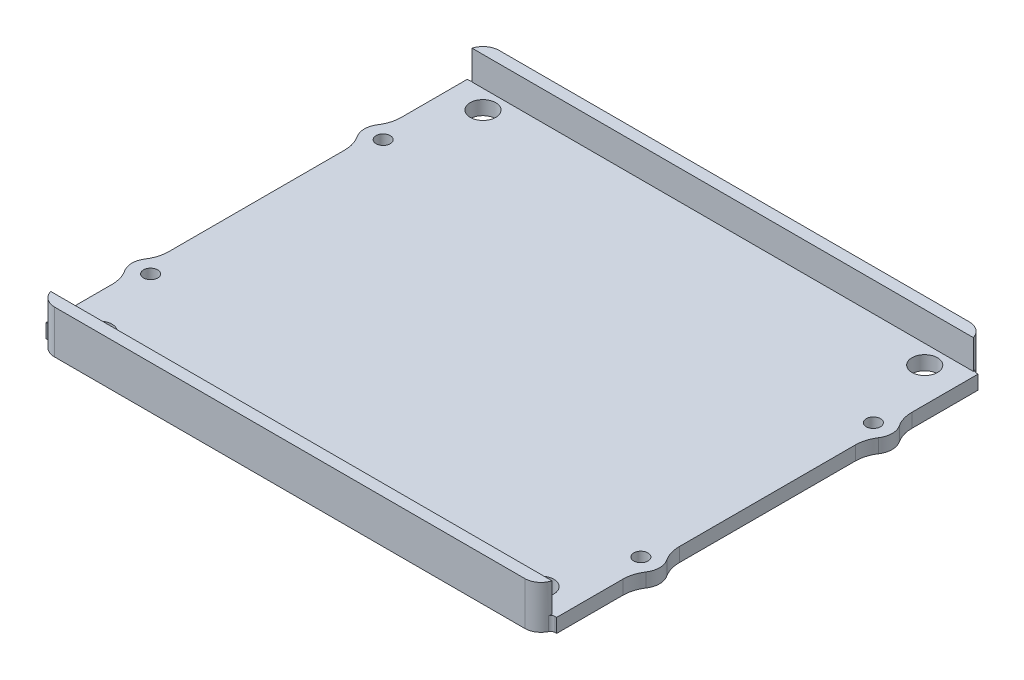
SolidWorks part; units mm, degrees
material "Hexcel AS4C (3000 Filaments)"
ref_plane "Front Plane" through (0, 0, 0) normal (0, 0, 1) x (1, 0, 0)
ref_plane "Top Plane" through (0, 0, 0) normal (0, 1, 0) x (1, 0, 0)
ref_plane "Right Plane" through (0, 0, 0) normal (1, 0, 0) x (0, 0, -1)
sketch "Sketch1" plane through (0, 0, 0) normal (0, 1, 0) x (1, 0, 0)
  line L1 (-50.55, -45.3) -> (50.55, -45.3)
  line L3 (-50.55, 45.3) -> (50.55, 45.3)
  line L7 (-50.55, 47.8) -> (50.55, 47.8)
  line L9 (-50.55, -47.8) -> (50.55, -47.8)
  line L10 (-50.55, 45.3) -> (-53.9041, 45.3)
  line L11 (-54.05, -44.3) -> (-54.05, 44.3) construction
  line L12 (-51.55, -44.3) -> (-51.55, 44.3) construction
  line L14 (-50.55, -45.3) -> (-53.9041, -45.3)
  line L16 (50.55, 45.3) -> (53.9041, 45.3)
  line L17 (50.55, -45.3) -> (53.9041, -45.3)
  line L18 (54.05, -44.3) -> (54.05, 44.3) construction
  line L19 (51.55, -44.3) -> (51.55, 44.3) construction
  arc A4 (-53.9041, 45.3) -> (-50.55, 47.8) centre (-50.55, 44.3) cw
  arc A5 (50.55, 47.8) -> (53.9041, 45.3) centre (50.55, 44.3) cw
  arc A6 (50.55, -47.8) -> (53.9041, -45.3) centre (50.55, -44.3) ccw
  arc A7 (-50.55, -47.8) -> (-53.9041, -45.3) centre (-50.55, -44.3) cw
  arc A8 (-51.55, 44.3) -> (-50.55, 45.3) centre (-50.55, 44.3) cw construction
  arc A9 (-54.05, 44.3) -> (-50.55, 47.8) centre (-50.55, 44.3) cw construction
  arc A10 (-50.55, -47.8) -> (-54.05, -44.3) centre (-50.55, -44.3) cw construction
  arc A11 (-50.55, -45.3) -> (-51.55, -44.3) centre (-50.55, -44.3) cw construction
  arc A12 (50.55, 47.8) -> (54.05, 44.3) centre (50.55, 44.3) cw construction
  arc A13 (50.55, 45.3) -> (51.55, 44.3) centre (50.55, 44.3) cw construction
  arc A14 (50.55, -47.8) -> (54.05, -44.3) centre (50.55, -44.3) ccw construction
  arc A15 (50.55, -45.3) -> (51.55, -44.3) centre (50.55, -44.3) ccw construction
  point P0 (0, 0)
  dimension "D4" = 2.5
extrude "Boss-Extrude1" add sketch "Sketch1" along normal blind 7.8 contours L16 A5 L7 A4 L10 L3 | L1 L17 A6 L9 A7 L14
sketch "Sketch3" plane through (0, 0, 0) normal (0, 1, 0) x (1, 0, 0)
  line L1 (-50.55, 47.8) -> (50.55, 47.8)
  line L3 (-50.55, -47.8) -> (50.55, -47.8)
  line L6 (-54.5811, 45.3) -> (-54.9091, 45.3)
  line L7 (-54.9091, 45.3) -> (-54.9091, -45.3)
  line L8 (-54.9091, -45.3) -> (-54.5811, -45.3)
  line L10 (54.9091, -45.3) -> (54.5811, -45.3)
  line L11 (54.9091, 45.3) -> (54.9091, -45.3)
  line L12 (54.5811, 45.3) -> (54.9091, 45.3)
  arc A14 (-53.6853, -45.8556) -> (-50.55, -47.8) centre (-50.55, -44.3) ccw
  arc A15 (-53.6853, 45.8556) -> (-50.55, 47.8) centre (-50.55, 44.3) cw
  arc A16 (50.55, 47.8) -> (53.6853, 45.8556) centre (50.55, 44.3) cw
  arc A17 (50.55, -47.8) -> (53.6853, -45.8556) centre (50.55, -44.3) ccw
  arc A18 (-53.6853, 45.8556) -> (-54.5811, 45.3) centre (-54.5811, 46.3) cw
  arc A19 (-53.6853, -45.8556) -> (-54.5811, -45.3) centre (-54.5811, -46.3) ccw
  arc A20 (53.6853, -45.8556) -> (54.5811, -45.3) centre (54.5811, -46.3) cw
  arc A21 (53.6853, 45.8556) -> (54.5811, 45.3) centre (54.5811, 46.3) ccw
  point P22 (-53.9041, 45.3)
  point P25 (-53.9041, -45.3)
  dimension "D2" = 1
  dimension "D1" = 1.005
extrude "Boss-Extrude2" add sketch "Sketch3" along normal mid plane 3
sketch "Sketch5" plane through (0, 1.5, 0) normal (0, 1, 0) x (1, 0, 0)
  circle A0 centre (-47.5, 41.25) radius 1.6
  circle A1 centre (47.5, 41.25) radius 1.6
  circle A2 centre (47.5, -41.25) radius 1.6
  circle A3 centre (-47.5, -41.25) radius 1.6
  dimension "D1" = 3.2
extrude "Cut-Extrude1" cut sketch "Sketch5" against normal through all
sketch "Sketch6" plane through (0, 1.5, 0) normal (0, 1, 0) x (1, 0, 0)
  line L0 (-54.9091, 45.3) -> (-54.9091, -45.3) construction
  circle A0 centre (-52.7091, 25) radius 1.525
  circle A1 centre (52.7091, 25) radius 1.525
  circle A2 centre (52.7091, -25) radius 1.525
  circle A3 centre (-52.7091, -25) radius 1.525
  dimension "D1" = 3.05
  dimension "D2" = 25
  dimension "D3" = 2.2
extrude "Cut-Extrude2" cut sketch "Sketch6" against normal through all
sketch "Sketch7" plane through (0, 0, 0) normal (0, 1, 0) x (1, 0, 0)
  circle A20 centre (-52.7091, 25) radius 4.025
  circle A21 centre (-52.7091, 25) radius 4.025
  circle A23 centre (-52.7091, -25) radius 4.025
  circle A24 centre (-52.7091, -25) radius 4.025
  circle A26 centre (52.7091, 25) radius 4.025
  circle A27 centre (52.7091, 25) radius 4.025
  circle A29 centre (52.7091, -25) radius 4.025
  circle A30 centre (52.7091, -25) radius 4.025
  circle A32 centre (-52.7091, 25) radius 1.525
  circle A33 centre (-52.7091, 25) radius 1.525
  circle A35 centre (-52.7091, -25) radius 1.525
  circle A36 centre (-52.7091, -25) radius 1.525
  circle A38 centre (52.7091, 25) radius 1.525
  circle A39 centre (52.7091, 25) radius 1.525
  circle A41 centre (52.7091, -25) radius 1.525
  circle A42 centre (52.7091, -25) radius 1.525
  dimension "D1" = 2.5
  dimension "D2" = 2.5
  dimension "D3" = 2.5
  dimension "D4" = 2.5
  dimension "D5" = 0
  dimension "D6" = 0
  dimension "D7" = 0
  dimension "D8" = 0
extrude "Boss-Extrude3" add sketch "Sketch7" along normal mid plane 3
fillet "Fillet1" radius 7 8 edges at (-54.9091, 0, 28.3706) (-54.9091, 0, 21.6294) (-54.9091, 0, -21.6294) (-54.9091, 0, -28.3706) (54.9091, 0, -28.3706) (54.9091, 0, -21.6294) (54.9091, 0, 21.6294) (54.9091, 0, 28.3706)
sketch "Sketch8" plane through (0, 1.5, 0) normal (0, 1, 0) x (1, 0, 0)
  circle A0 centre (-47.5, -41.25) radius 2.75
  circle A1 centre (-47.5, 41.25) radius 2.75
  circle A2 centre (47.5, 41.25) radius 2.75
  circle A3 centre (47.5, -41.25) radius 2.75
  dimension "D1" = 5.5
extrude "Cut-Extrude3" cut sketch "Sketch8" against normal blind 3
